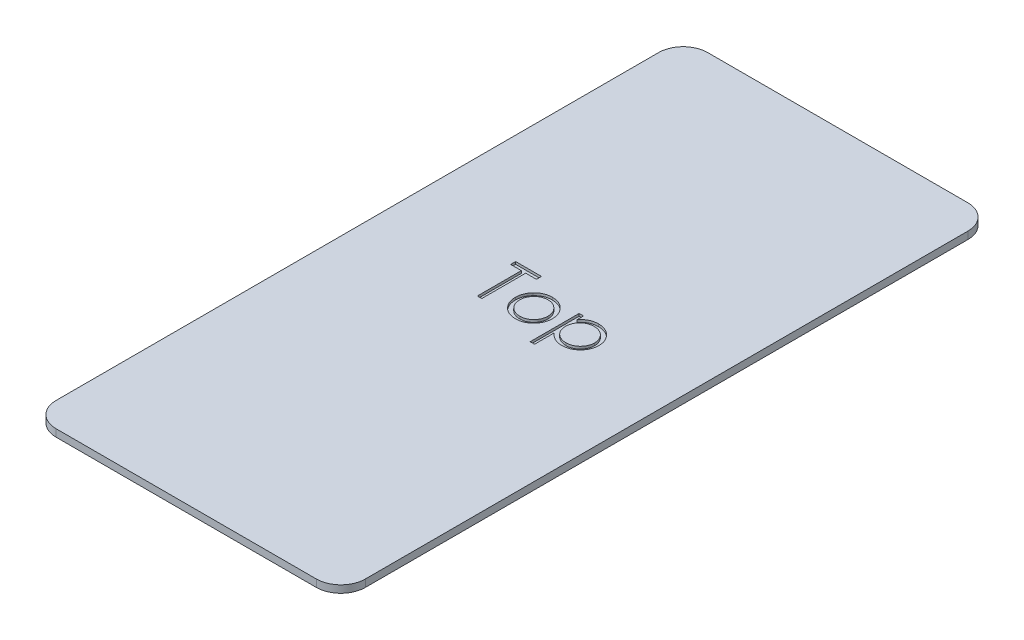
SolidWorks part; units mm, degrees
ref_plane "Front Plane" through (0, 0, 0) normal (0, 0, 1) x (1, 0, 0)
ref_plane "Top Plane" through (0, 0, 0) normal (0, 1, 0) x (1, 0, 0)
ref_plane "Right Plane" through (0, 0, 0) normal (1, 0, 0) x (0, 0, -1)
sketch "Sketch1" plane through (0, 0, 0) normal (0, 1, 0) x (1, 0, 0)
  line L1 (-63.105, -132.955) -> (63.105, -132.955)
  line L2 (-63.105, -132.955) -> (-63.105, 132.955)
  line L3 (-63.105, 132.955) -> (63.105, 132.955)
  line L4 (63.105, -132.955) -> (63.105, 132.955)
  line L5 (-63.105, -132.955) -> (63.105, 132.955) construction
  line L6 (-63.105, 132.955) -> (63.105, -132.955) construction
  point P0 (0, 0)
  dimension "D1" = 265.91
  dimension "D2" = 126.21
extrude "Boss-Extrude1" add sketch "Sketch1" along normal blind 3
sketch "Sketch2" plane through (0, 3, 0) normal (0, 1, 0) x (1, 0, 0)
  text T0 "Top" font "Century Gothic" height 20
extrude "Cut-Extrude1" cut sketch "Sketch2" against normal blind 1
fillet "Fillet1" radius 10 4 edges at (-63.105, 1.5, 132.955) (-63.105, 1.5, -132.955) (63.105, 1.5, -132.955) (63.105, 1.5, 132.955)
